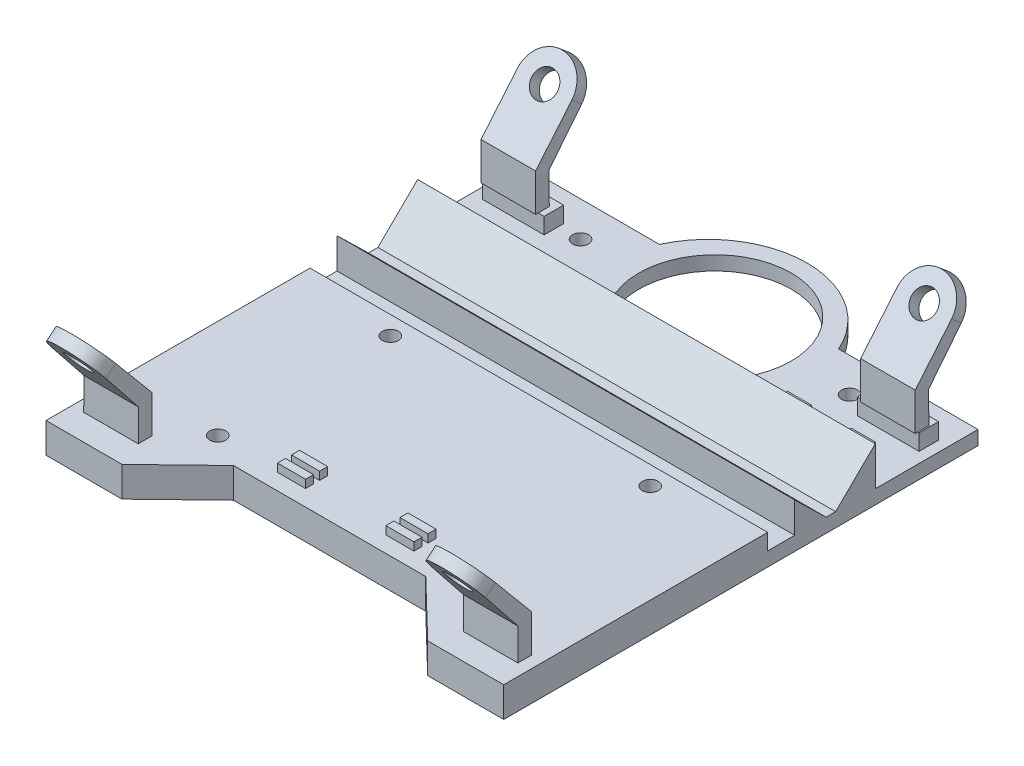
SolidWorks part; units mm, degrees
ref_plane "Ebene vorne" through (0, 0, 0) normal (0, 0, 1) x (1, 0, 0)
ref_plane "Ebene oben" through (0, 0, 0) normal (0, 1, 0) x (1, 0, 0)
ref_plane "Ebene rechts" through (0, 0, 0) normal (1, 0, 0) x (0, 0, -1)
sketch "Skizze1" plane through (0, 0, 0) normal (0, 1, 0) x (1, 0, 0)
  line L1 (0, 0) -> (57, 0)
  line L2 (0, 0) -> (0, 60)
  line L3 (0, 60) -> (57, 60)
  line L4 (57, 0) -> (57, 60)
  dimension "D1" = 57
  dimension "D2" = 60
extrude "Aufsatz-Linear austragen1" add sketch "Skizze1" against normal blind 1.75
sketch "Skizze3" plane through (0, 0, 0) normal (0, 1, 0) x (1, 0, 0)
  line L0 (57, 60) -> (0, 60) construction
  line L2 (57, 0) -> (57, 60) construction
  circle A0 centre (28.5, 48) radius 9.4954
  dimension "D1" = 12
  dimension "D2" = 28.5
extrude "Schnitt-Linear austragen1" cut sketch "Skizze3" against normal blind 2
sketch "Skizze4" plane through (0, 0, 0) normal (0, 1, 0) x (1, 0, 0)
  line L0 (0, 60) -> (0, 0) construction
  line L1 (57, 0) -> (0, 0)
  line L2 (57, 0) -> (57, 26.0545)
  line L3 (57, 26.0545) -> (0, 26.0545)
  line L4 (0, 0) -> (0, 26.0545)
extrude "Aufsatz-Linear austragen2" add sketch "Skizze4" along normal blind 2
sketch "Skizze5" plane through (0, 2, 0) normal (0, 1, 0) x (1, 0, 0)
  circle A0 centre (12.3153, 23.7449) radius 1
  circle A1 centre (12.3153, 2.2449) radius 1
  dimension "D1" = 2
  dimension "D2" = 2
extrude "Schnitt-Linear austragen2" cut sketch "Skizze5" against normal blind 4
ref_plane "Ebene1" through (28.5, 0, 0) normal (-1, 0, 0) x (0, 0, 1)
mirror "Spiegeln1" about plane through (28.5, 0, 0) normal (-1, 0, 0) of "Schnitt-Linear austragen2"
sketch "Skizze8" plane through (0, 0, 0) normal (-1, 0, 0) x (0, 0, 1)
  line L1 (-29.4199, 3.8153) -> (-33.3253, 0)
  line L4 (-60, 0) -> (-26.0545, 0) construction
  line L8 (-33.3253, 0) -> (-29.4199, 0)
  line L10 (-29.4199, 0) -> (-29.4199, 3.8153)
extrude "Aufsatz-Linear austragen3" add sketch "Skizze8" against normal blind 57
sketch "Skizze10" plane through (0, 0, 0) normal (0, 1, 0) x (1, 0, 0)
  line L1 (57, 60) -> (0, 60) construction
  line L2 (57, 33.3253) -> (57, 60) construction
  line L3 (0, 60) -> (0, 33.3253) construction
  circle A0 centre (45.25, 48) radius 1
  circle A1 centre (11.75, 48) radius 1
  dimension "D1" = 12
  dimension "D2" = 12
  dimension "D3" = 11.75
  dimension "D4" = 11.75
extrude "Schnitt-Linear austragen3" cut sketch "Skizze10" against normal blind 2
sketch "Skizze11" plane through (0, 0, 0) normal (-1, 0, 0) x (0, 0, 1)
  line L0 (-39.4583, 4.8503) -> (-39.4583, 0)
  line L1 (-60, 0) -> (-33.3253, 0) construction
  line L2 (-39.4583, 0) -> (-34.5117, 0)
  line L3 (-34.5117, 0) -> (-39.4583, 4.8503)
extrude "Aufsatz-Linear austragen4" add sketch "Skizze11" against normal blind 57
sketch "Skizze13" plane through (0, 0, 0) normal (0, 1, 0) x (1, 0, 0)
  line L0 (53, 42.5) -> (50, 42.5)
  line L1 (50, 42.5) -> (50, 43.5)
  line L2 (50, 43.5) -> (53, 43.5)
  line L5 (45, 42.5) -> (45, 43.5)
  line L6 (45, 43.5) -> (42, 43.5)
  line L7 (42, 43.5) -> (42, 42.5)
  line L8 (42, 42.5) -> (45, 42.5)
  line L9 (53, 40.75) -> (50, 40.75)
  line L10 (50, 40.75) -> (50, 41.75)
  line L11 (50, 41.75) -> (53, 41.75)
  line L12 (53, 41.75) -> (53, 40.75)
  line L14 (45, 41.75) -> (42, 41.75)
  line L15 (42, 41.75) -> (42, 40.75)
  line L16 (42, 40.75) -> (45, 40.75)
  line L17 (45, 40.75) -> (45, 41.75)
  line L18 (57, 60) -> (0, 60) construction
  line L19 (57, 39.4583) -> (57, 60) construction
  line L20 (53, 42.5) -> (53, 43.5)
  dimension "D1" = 0.75
  dimension "D2" = 1
  dimension "D3" = 1
  dimension "D4" = 0.75
  dimension "D5" = 16.5
  dimension "D6" = 16.5
  dimension "D7" = 4
  dimension "D8" = 1
  dimension "D9" = 3
  dimension "D10" = 1
  dimension "D11" = 3
  dimension "D12" = 3
  dimension "D13" = 16.5
extrude "Aufsatz-Linear austragen6" add sketch "Skizze13" along normal blind 1
sketch "Skizze16" plane through (0, 2, 0) normal (0, 1, 0) x (1, 0, 0)
  line L5 (20, 2) -> (23.5, 2)
  line L6 (20, 2) -> (20, 3)
  line L7 (20, 3) -> (23.5, 3)
  line L8 (23.5, 2) -> (23.5, 3)
  line L9 (33.5, 2) -> (37, 2)
  line L11 (33.5, 2) -> (33.5, 3)
  line L12 (33.5, 3) -> (37, 3)
  line L13 (37, 2) -> (37, 3)
  line L14 (20, 3.75) -> (23.5, 3.75)
  line L15 (20, 3.75) -> (20, 4.75)
  line L16 (20, 4.75) -> (23.5, 4.75)
  line L17 (23.5, 3.75) -> (23.5, 4.75)
  line L18 (33.5, 3.75) -> (37, 3.75)
  line L19 (33.5, 3.75) -> (33.5, 4.75)
  line L20 (33.5, 4.75) -> (37, 4.75)
  line L21 (37, 3.75) -> (37, 4.75)
  line L22 (0, 0) -> (57, 0) construction
  line L23 (0, 0) -> (57, 0) construction
  line L24 (0, 26.0545) -> (0, 0) construction
  point P20 (23.5, 2.5)
  dimension "D1" = 1
  dimension "D2" = 1
  dimension "D3" = 1
  dimension "D4" = 1
  dimension "D5" = 3.5
  dimension "D6" = 3.5
  dimension "D7" = 3.5
  dimension "D8" = 3.5
  dimension "D9" = 0.75
  dimension "D10" = 0.75
  dimension "D11" = 2
  dimension "D12" = 2
  dimension "D13" = 10
  dimension "D14" = 0
  dimension "D15" = 20
extrude "Aufsatz-Linear austragen9" add sketch "Skizze16" along normal blind 1
sketch "Skizze20" plane through (57, 0, 0) normal (1, 0, 0) x (0, 0, -1)
  line L0 (0, 2) -> (0, 7.048)
  line L1 (0, 2) -> (26.0545, 2) construction
  line L2 (0, 7.048) -> (4, 7.048)
  line L3 (4, 7.048) -> (4, 2)
  line L4 (4, 2) -> (4, 21.5) construction
  line L5 (4, 2) -> (0, 2)
  dimension "D1" = 4
  dimension "D2" = 4
sketch "Skizze24" plane through (0, 2, 0) normal (0, 1, 0) x (1, 0, 0)
  line L0 (57, 0) -> (57, -15.9632)
  line L1 (57, -15.9632) -> (46.4704, -5.7952)
  line L2 (46.4704, -5.7952) -> (40.4691, 0)
  line L3 (0, 0) -> (57, 0) construction
  line L6 (40.4691, 0) -> (57, 0)
extrude "Aufsatz-Linear austragen11" add sketch "Skizze24" against normal blind 3.75
mirror "Spiegeln2" about plane through (28.5, 0, 0) normal (-1, 0, 0) of "Aufsatz-Linear austragen11"
sketch "Skizze25" plane through (0, 2, 0) normal (0, 1, 0) x (1, 0, 0)
  line L14 (48.7359, -1.2853) -> (55.5359, -1.2853)
  line L15 (48.7359, -1.2853) -> (48.7359, -5.9633)
  line L16 (48.7359, -5.9633) -> (55.5359, -5.9633)
  line L17 (55.5359, -1.2853) -> (55.5359, -5.9633)
  dimension "D1" = 6.8
extrude "Aufsatz-Linear austragen12" add sketch "Skizze25" along normal blind 13
sketch "Skizze26" plane through (55.5359, 0, 0) normal (1, 0, 0) x (0, 0, -1)
  line L0 (-5.9633, 7.8681) -> (-12.2355, 7.8681)
  line L1 (-5.9633, 15) -> (-5.9633, 2) construction
  line L2 (-12.2355, 7.8681) -> (-12.2355, 15)
  line L3 (-12.2355, 15) -> (-5.9633, 15)
  line L4 (-5.9633, 15) -> (-5.9633, 7.8681)
  point P8 (-5.9957, 7.8681)
extrude "Aufsatz-Linear austragen13" add sketch "Skizze26" against normal blind 6.8
sketch "Skizze27" plane through (55.5359, 0, 0) normal (1, 0, 0) x (0, 0, -1)
  line L0 (-12.2355, 15) -> (-1.2853, 15) construction
  line L1 (-10.7685, 15) -> (-3.5522, 5.947)
  line L2 (-3.5522, 5.947) -> (-3.5907, 2)
  line L3 (-15.9632, 2) -> (26.0545, 2) construction
  line L4 (-3.5907, 2) -> (-6.081, 2)
  line L5 (-6.081, 2) -> (-5.9633, 7.8681)
  line L6 (-5.9633, 7.8681) -> (-12.2355, 7.8681)
  line L7 (-12.2355, 7.8681) -> (-12.2355, 15)
  line L8 (-12.2355, 15) -> (-10.7685, 15)
  circle A0 centre (12.9949, 7) radius 17.3229 construction
extrude "Schnitt-Linear austragen5" cut sketch "Skizze27" against normal blind 6.8
sketch "Skizze28" plane through (55.5359, 0, 0) normal (1, 0, 0) x (0, 0, -1)
  line L0 (-9.8552, 13.8542) -> (-8.6758, 14.7943)
  line L1 (-3.5522, 5.947) -> (-10.7685, 15) construction
  line L2 (-8.6758, 14.7943) -> (-1.8918, 6.6863)
  line L3 (-1.8918, 6.6863) -> (-1.8918, 2)
  line L4 (-15.9632, 2) -> (26.0545, 2) construction
  line L5 (-1.8918, 2) -> (-1.2415, 2)
  line L6 (-1.2415, 2) -> (-1.2415, 15.4301)
  line L7 (-1.2415, 15.4301) -> (-11.1128, 15.4301)
  line L8 (-11.1128, 15.4301) -> (-9.8552, 13.8542)
  point P10 (-11.1208, 15.433)
  point P12 (-11.1159, 15.4301)
  point P13 (-10.575, 14.7572)
  point P14 (-9.8552, 13.8542)
extrude "Schnitt-Linear austragen6" cut sketch "Skizze28" against normal blind 6.8 contours L2 L3 L5 L6 L7 L8 L0
sketch "Skizze29" plane through (0, 1.8223, -2.178) normal (0, 0.6417, -0.7669) x (-1, 0, 0)
  line L8 (-55.5359, 13.3838) -> (-55.5359, 17.0838)
  line L9 (-55.5359, 16.9138) -> (-55.5359, 6.342) construction
  line L10 (-55.5359, 17.0838) -> (-48.7359, 17.0838)
  line L11 (-48.7359, 17.0838) -> (-48.7359, 13.3838)
  line L12 (-48.7359, 16.9138) -> (-48.7359, 6.342) construction
  arc A1 (-48.7359, 13.3838) -> (-55.5359, 13.3838) centre (-52.1359, 13.3838) ccw
  point P9 (-48.7359, 17.1245)
  point P10 (-55.5903, 13.8401)
  point P11 (-48.7359, 17.1245)
  dimension "D1" = 3.4
  dimension "D2" = 3.7
  dimension "D3" = 3.53
extrude "Schnitt-Linear austragen8" cut sketch "Skizze29" against normal blind 3.8
sketch "Skizze30" plane through (0, 1.8223, -2.178) normal (0, 0.6417, -0.7669) x (-1, 0, 0)
  circle A0 centre (-52.1359, 13.3838) radius 1.6
  arc A1 (-48.7359, 13.3838) -> (-55.5359, 13.3838) centre (-52.1359, 13.3838) ccw construction
  dimension "D1" = 3.2
  dimension "D2" = 0
extrude "Schnitt-Linear austragen9" cut sketch "Skizze30" against normal blind 3.8
mirror "Spiegeln6" about plane through (28.5, 0, 0) normal (-1, 0, 0) of "Schnitt-Linear austragen9", "Schnitt-Linear austragen8", "Schnitt-Linear austragen6", "Schnitt-Linear austragen5", "Aufsatz-Linear austragen13", "Aufsatz-Linear austragen12"
ref_plane "Ebene2" through (0, 0, -22) normal (0, 0, -1) x (-1, 0, 0)
sketch "Skizze31" plane through (0, 0, 0) normal (0, 1, 0) x (1, 0, 0)
  line L1 (48, 46.2086) -> (55.6975, 46.2086)
  line L2 (48, 46.2086) -> (48, 48.6381)
  line L3 (48, 48.6381) -> (55.6975, 48.6381)
  line L4 (55.6975, 46.2086) -> (55.6975, 48.6381)
extrude "Aufsatz-Linear austragen15" add sketch "Skizze31" along normal blind 2
mirror "Spiegeln8" about plane through (0, 0, -22) normal (0, 0, -1) of "Schnitt-Linear austragen9", "Schnitt-Linear austragen8", "Schnitt-Linear austragen6", "Schnitt-Linear austragen5", "Aufsatz-Linear austragen13", "Aufsatz-Linear austragen12"
mirror "Spiegeln9" about plane through (28.5, 0, 0) normal (-1, 0, 0) of "Spiegeln8", "Aufsatz-Linear austragen15", "Aufsatz-Linear austragen12", "Schnitt-Linear austragen5", "Schnitt-Linear austragen6", "Schnitt-Linear austragen8", "Schnitt-Linear austragen9"
sketch "Skizze36" plane through (0, 0, 0) normal (0, 1, 0) x (1, 0, 0)
  line L0 (0, 52.369) -> (17.2084, 52.369)
  line L1 (57, 52.2455) -> (57, 60)
  line L2 (57, 60) -> (0, 60)
  line L3 (0, 60) -> (0, 52.369)
  line L4 (57, 52.2455) -> (39.6409, 52.2455)
  arc A0 (17.2084, 52.369) -> (39.6409, 52.2455) centre (28.3968, 47.2564) cw
  point P10 (0, 0)
extrude "Schnitt-Linear austragen10" cut sketch "Skizze36" against normal blind 10 contours L4 A0 L0 L3 L2 L1
sketch "Skizze37" plane through (0, 2, 0) normal (0, 1, 0) x (1, 0, 0)
  line L0 (0, -6.8214) -> (9.5761, -6.8214)
  line L1 (9.5761, -6.8214) -> (0, -15.9632)
  line L2 (0, -15.9632) -> (0, -6.8214)
extrude "Schnitt-Linear austragen11" cut sketch "Skizze37" against normal blind 10
mirror "Spiegeln10" about plane through (28.5, 0, 0) normal (-1, 0, 0) of "Schnitt-Linear austragen11"
ref_plane "Ebene14" through (0, 0.4646, -47.6057) normal (0, 0.0098, -1) x (-1, 0, 0)
